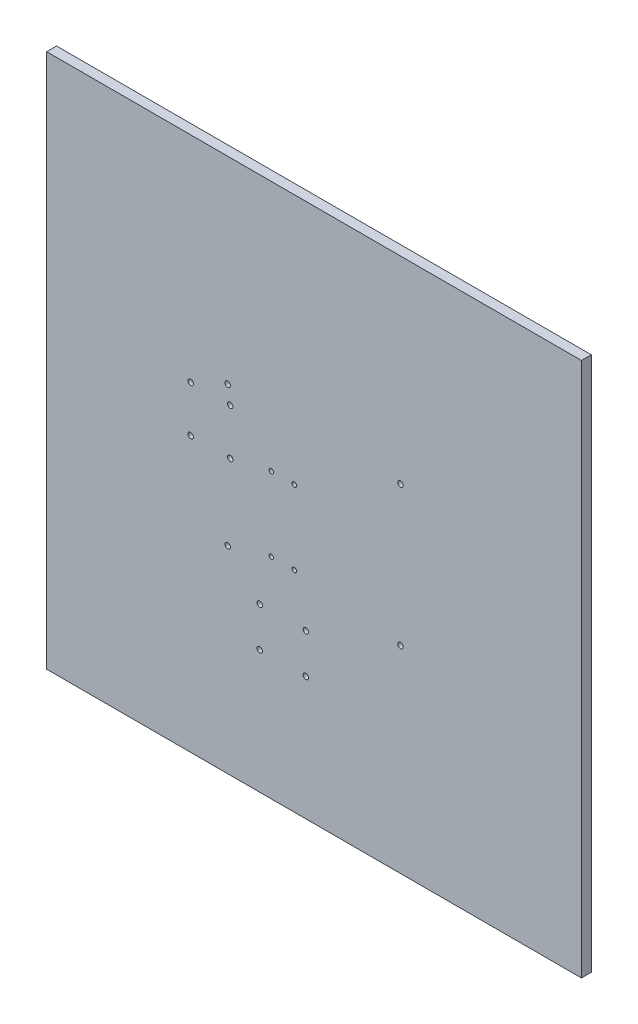
SolidWorks part; units mm, degrees
material "6061-T6 (SS)"
ref_plane "Front Plane" through (0, 0, 0) normal (0, 0, 1) x (1, 0, 0)
ref_plane "Top Plane" through (0, 0, 0) normal (0, 1, 0) x (1, 0, 0)
ref_plane "Right Plane" through (0, 0, 0) normal (1, 0, 0) x (0, 0, -1)
sketch "Sketch1" plane through (0, 0, 0) normal (0, 0, 1) x (1, 0, 0)
  line L1 (-325, -325) -> (325, -325)
  line L2 (-325, -325) -> (-325, 325)
  line L3 (-325, 325) -> (325, 325)
  line L4 (325, -325) -> (325, 325)
extrude "Bench_Plate" add sketch "Sketch1" along normal blind 12
sketch "Sketch2" plane through (0, 0, 12) normal (0, 0, 1) x (1, 0, 0)
  circle A0 centre (-105, -85) radius 3.3
  circle A1 centre (-105, 85) radius 3.3
  circle A2 centre (105, -85) radius 3.3
  circle A3 centre (105, 85) radius 3.3
  circle A4 centre (-149.9428, 8.5) radius 3.3
  circle A5 centre (-101.9428, 8.5) radius 3.3
  circle A6 centre (-149.9428, 64.5) radius 3.3
  circle A7 centre (-101.9428, 64.5) radius 3.3
  circle A8 centre (-10, -174.9952) radius 3.3
  circle A9 centre (-10, -126.9952) radius 3.3
  circle A10 centre (-66, -174.9952) radius 3.3
  circle A11 centre (-66, -126.9952) radius 3.3
extrude "Bench_M6_Anchor_Holes_12x_D6p6" cut sketch "Sketch2" against normal blind 12
sketch "Sketch3" plane through (0, 0, 12) normal (0, 0, 1) x (1, 0, 0)
  circle A0 centre (-52, -70) radius 2.75
  circle A1 centre (-52, 20) radius 2.75
  circle A2 centre (-24, -70) radius 2.75
  circle A3 centre (-24, 20) radius 2.75
extrude "Bench_M5_SupportPost_Holes_4x_D5p5" cut sketch "Sketch3" against normal blind 12
